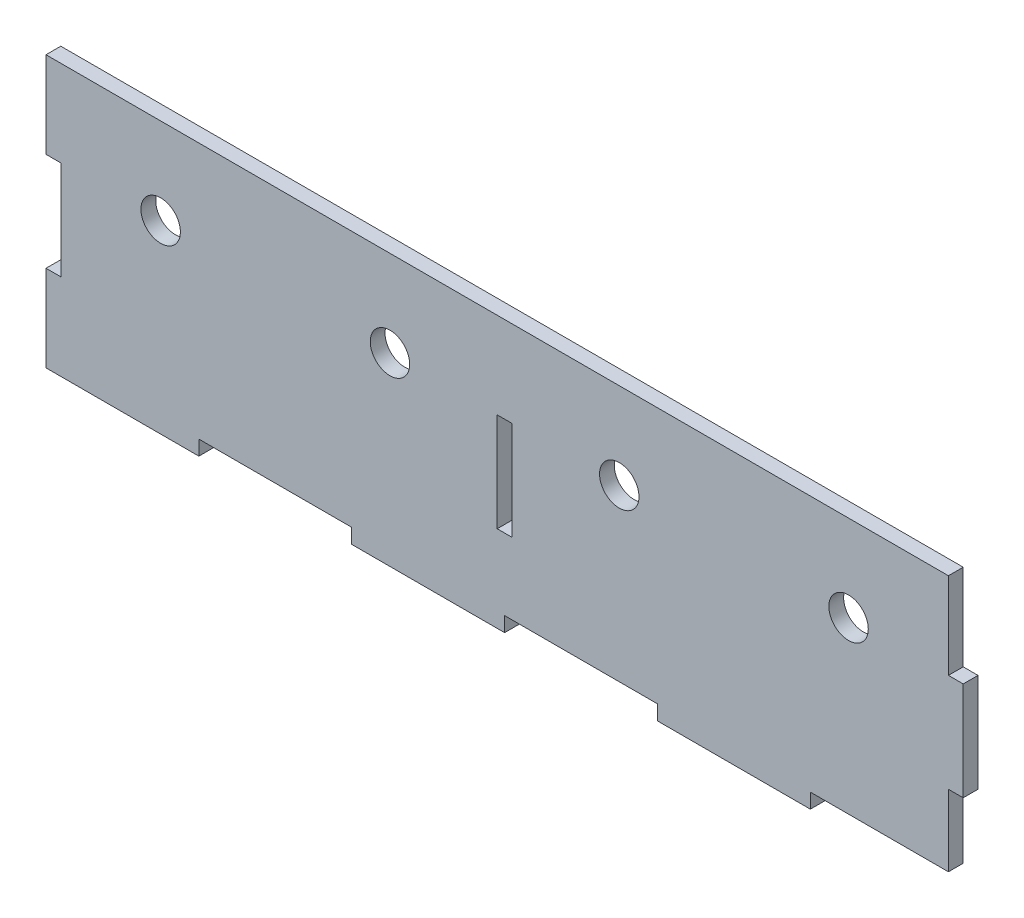
SolidWorks part; units mm, degrees
ref_plane "Front Plane" through (0, 0, 0) normal (0, 0, 1) x (1, 0, 0)
ref_plane "Top Plane" through (0, 0, 0) normal (0, 1, 0) x (1, 0, 0)
ref_plane "Right Plane" through (0, 0, 0) normal (1, 0, 0) x (0, 0, -1)
sketch "Sketch1" plane through (0, 0, 0) normal (0, 0, 1) x (1, 0, 0)
  line L0 (-93, 10) -> (-90, 10)
  line L1 (-93, -27.5) -> (93, -27.5)
  line L2 (-93, -27.5) -> (-93, 27.5)
  line L3 (-93, 27.5) -> (93, 27.5)
  line L4 (93, -27.5) -> (93, 27.5)
  line L5 (-93, -27.5) -> (93, 27.5) construction
  line L6 (-93, 27.5) -> (93, -27.5) construction
  line L7 (-90, 10) -> (-90, -10)
  line L8 (-90, -10) -> (-93, -10)
  line L9 (93, -10) -> (90, -10)
  line L10 (90, -10) -> (90, -27.5)
  line L11 (93, 10) -> (90, 10)
  line L12 (90, 10) -> (90, 27.5)
  line L14 (-62, -27.5) -> (-62, -24.5)
  line L15 (-62, -24.5) -> (-31, -24.5)
  line L16 (-31, -24.5) -> (-31, -27.5)
  line L17 (-93, -27.5) -> (0, -27.5)
  line L18 (0, -27.5) -> (0, -24.5)
  line L19 (0, -24.5) -> (31, -24.5)
  line L20 (31, -24.5) -> (31, -27.5)
  line L21 (-93, -27.5) -> (-93, 27.5)
  line L22 (62, -27.5) -> (62, -24.5)
  line L23 (62, -24.5) -> (93, -24.5)
  line L24 (93, -24.5) -> (93, -27.5)
  line L25 (-93, 27.5) -> (0, 27.5)
  line L26 (-1.5, -10) -> (1.5, -10)
  line L27 (-1.5, -10) -> (-1.5, 10)
  line L28 (-1.5, 10) -> (1.5, 10)
  line L29 (1.5, -10) -> (1.5, 10)
  line L30 (-1.5, -10) -> (1.5, 10) construction
  line L31 (-1.5, 10) -> (1.5, -10) construction
  circle A0 centre (-69.75, 10) radius 4
  circle A1 centre (-23.25, 10) radius 4
  circle A2 centre (23.25, 10) radius 4
  circle A3 centre (69.75, 10) radius 4
  point P0 (0, 0)
  point P15 (0, 0)
  point P33 (-46.5, 0)
  dimension "D17" = 17.5
  dimension "D18" = 8
  dimension "D20" = 8
  dimension "D27" = 8
  dimension "D28" = 8
  dimension "D1" = 55
  dimension "D2" = 186
  dimension "D3" = 20
  dimension "D4" = 3
  dimension "D5" = 17.5
  dimension "D6" = 3
  dimension "D7" = 3
  dimension "D8" = 31
  dimension "D9" = 31
  dimension "D10" = 31
  dimension "D11" = 31
  dimension "D12" = 31
  dimension "D13" = 31
  dimension "D14" = 3
  dimension "D15" = 20
  dimension "D16" = 3
  dimension "D19" = 23.25
  dimension "D21" = 17.5
  dimension "D22" = 46.5
  dimension "D23" = 46.5
  dimension "D24" = 46.5
  dimension "D25" = 17.5
  dimension "D26" = 17.5
extrude "Boss-Extrude1" add sketch "Sketch1" along normal blind 3 contours L23 L24 L1 L10 L9 L4 L11 L12 L3 L2 L0 L7 L8 L14 L15 L16 L18 L19 L20 L22 L29 L26 L27 L28
